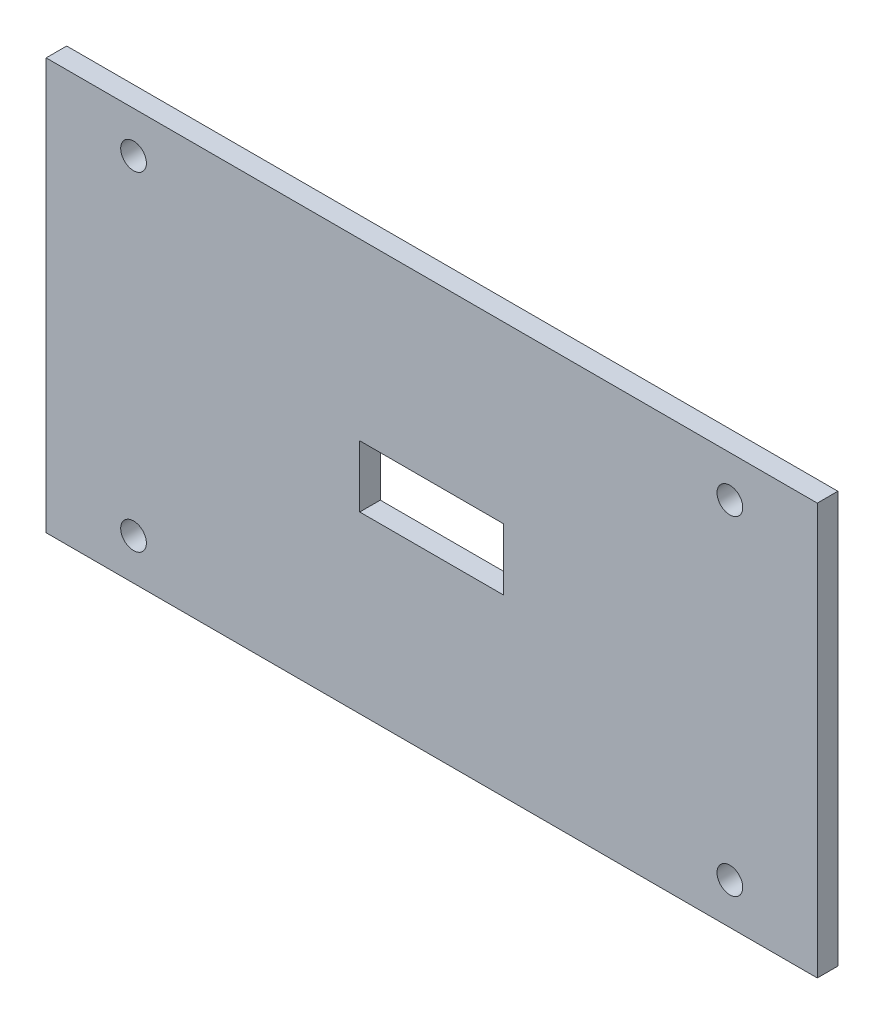
SolidWorks part; units mm, degrees
ref_plane "Plano frontal" through (0, 0, 0) normal (0, 0, 1) x (1, 0, 0)
ref_plane "Plano superior" through (0, 0, 0) normal (0, 1, 0) x (1, 0, 0)
ref_plane "Plano direito" through (0, 0, 0) normal (1, 0, 0) x (0, 0, -1)
sketch "Esboço1" plane through (0, 0, 0) normal (0, 0, 1) x (1, 0, 0)
  line L1 (-49.5557, 47.9499) -> (100.4443, 47.9499)
  line L2 (-49.5557, 47.9499) -> (-49.5557, -32.0501)
  line L3 (-49.5557, -32.0501) -> (100.4443, -32.0501)
  line L4 (100.4443, 47.9499) -> (100.4443, -32.0501)
  line L5 (11.4443, 13.9499) -> (39.4443, 13.9499)
  line L6 (11.4443, 13.9499) -> (11.4443, 1.9499)
  line L7 (11.4443, 1.9499) -> (39.4443, 1.9499)
  line L8 (39.4443, 13.9499) -> (39.4443, 1.9499)
  circle A0 centre (-32.5557, 39.9499) radius 2.5
  circle A1 centre (-32.5557, -24.0501) radius 2.5
  circle A4 centre (83.4443, 39.9499) radius 2.5
  circle A5 centre (83.4443, -24.0501) radius 2.5
  dimension "D3" = 5
  dimension "D8" = 28
  dimension "D1" = 80
  dimension "D2" = 150
  dimension "D4" = 17
  dimension "D5" = 8
  dimension "D6" = 8
  dimension "D7" = 17
  dimension "D9" = 12
  dimension "D10" = 34
  dimension "D11" = 61
extrude "Ressalto-extrusão2" add sketch "Esboço1" along normal blind 4
